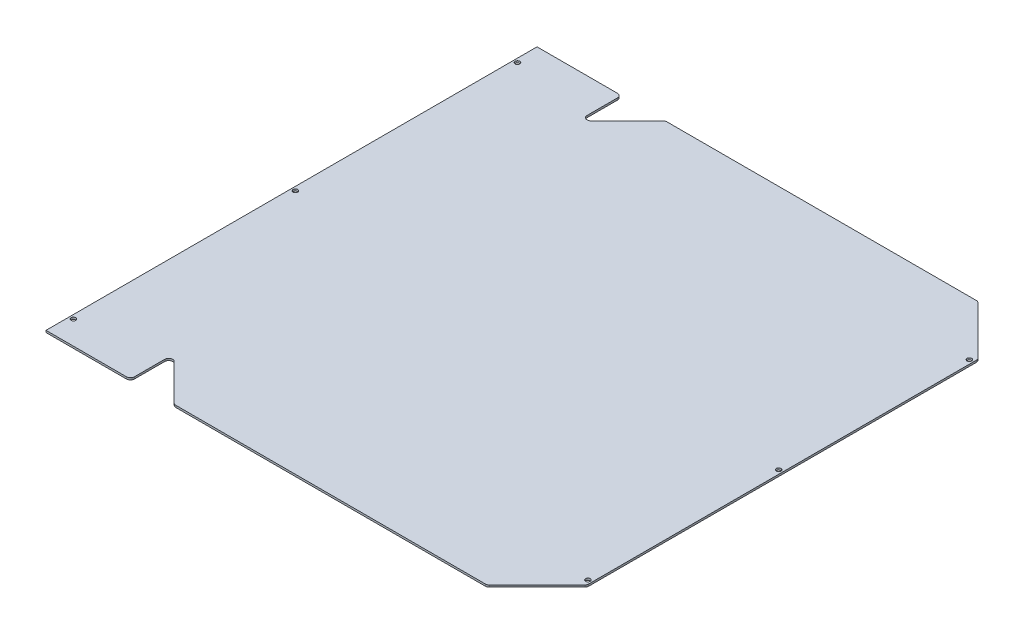
SolidWorks part; units mm, degrees
material "PC High Viscosity"
ref_plane "Front Plane" through (0, 0, 0) normal (0, 0, 1) x (1, 0, 0)
ref_plane "Top Plane" through (0, 0, 0) normal (0, 1, 0) x (1, 0, 0)
ref_plane "Right Plane" through (0, 0, 0) normal (1, 0, 0) x (0, 0, -1)
sketch "Sketch1" plane through (0, 0, 0) normal (0, 1, 0) x (1, 0, 0)
  line L0 (158.75, 199.39) -> (199.39, 158.75)
  line L1 (-199.39, 199.39) -> (199.39, 199.39)
  line L2 (-199.39, 199.39) -> (-199.39, -199.39)
  line L3 (-199.39, -199.39) -> (199.39, -199.39)
  line L4 (199.39, 199.39) -> (199.39, -199.39)
  line L5 (158.75, -199.39) -> (199.39, -158.75)
  line L6 (-130.81, 199.39) -> (-130.81, 163.83)
  line L7 (-130.81, 163.83) -> (-95.25, 199.39)
  line L9 (-130.81, -199.39) -> (-130.81, -163.83)
  line L10 (-130.81, -163.83) -> (-95.25, -199.39)
  point P0 (0, 0)
  point P6 (-199.39, 0)
  point P7 (196.215, 0)
  point P9 (0, 199.39)
  point P13 (-196.215, 0)
  point P27 (-196.215, -180.34)
  point P28 (196.215, 154.94)
  point P29 (196.215, -154.94)
  point P30 (-196.215, 180.34)
  dimension "D4" = 3.175
  dimension "D9" = 40.64
  dimension "D11" = 35.56
  dimension "D6" = 19.05
  dimension "D2" = 398.78
  dimension "D3" = 398.78
  dimension "D5" = 44.45
  dimension "D7" = 19.05
  dimension "D8" = 45
  dimension "D10" = 68.58
  dimension "D12" = 44.45
  dimension "D13" = 3.175
  dimension "D14" = 3.175
  dimension "D16" = 199.39
  dimension "D15" = 45
extrude "Boss-Extrude1" add sketch "Sketch1" against normal blind 1.5875
hole_wizard "#6 Clearance Hole1" positions "Sketch4" profile "Sketch5" hole size "#6" standard "ANSI Inch" end condition through all
sketch "Sketch4" plane through (0, -1.5875, 0) normal (0, -1, 0) x (-1, 0, 0)
  point P0 (196.215, 180.34)
  point P3 (196.215, -180.34)
  point P6 (-196.215, -154.94)
  point P9 (-196.215, 154.94)
  point P12 (196.215, 0)
  point P14 (-196.215, 0)
sketch "Sketch5" plane through (-196.215, -1.5875, -180.34) normal (1, 0, 0) x (0, 0, -1)
  line L0 (0, 0) -> (0, 1.5875)
  line L1 (0, 1.5875) -> (1.8986, 1.5875)
  line L2 (1.8986, 1.5875) -> (1.8986, 0)
  line L5 (1.8986, 0) -> (0, 0)
  line L11 (0, -6.35) -> (0, 107.95) construction
  dimension "Thru Hole Dia." = 3.7973
  dimension "Thru Hole Depth" = 1.5875
fillet "Fillet1" radius 3.175 10 edges at (158.75, -0.7937, -199.39) (199.39, -0.7937, -158.75) (199.39, -0.7937, 158.75) (158.75, -0.7937, 199.39) (-130.81, -0.7937, 163.83) (-130.81, -0.7937, 199.39) (-95.25, -0.7937, 199.39) (-95.25, -0.7937, -199.39) (-130.81, -0.7937, -199.39) (-130.81, -0.7937, -163.83)
